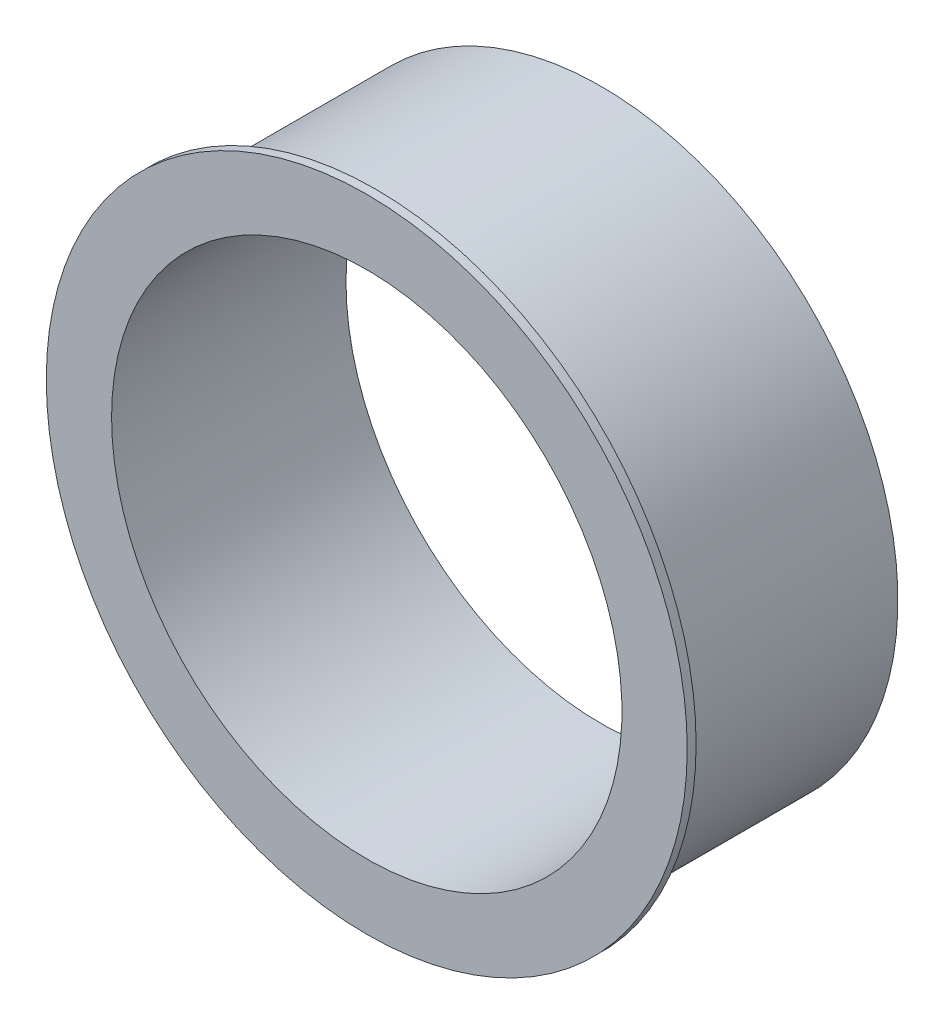
SolidWorks part; units mm, degrees
ref_plane "Front Plane" through (0, 0, 0) normal (1, 0, 0) x (0, 1, 0)
ref_plane "Top Plane" through (0, 0, 0) normal (0, 0, 1) x (0, 1, 0)
ref_plane "Right Plane" through (0, 0, 0) normal (0, 1, 0) x (-1, 0, 0)
sketch "Sketch1" plane through (0, 0, 0) normal (0, 1, 0) x (-1, 0, 0)
  line L0 (-43, -150) -> (-50, -150)
  line L1 (-50, -150) -> (-50, -112)
  line L2 (-50, -112) -> (-54, -112)
  line L3 (-54, -112) -> (-54, -110.5)
  line L4 (-54, -110.5) -> (-43, -110.5)
  line L5 (-43, -110.5) -> (-43, -150)
  line L6 (0, -500) -> (0, 500) construction
revolve "Revolve1" add sketch "Sketch1" angle 360 about L6
